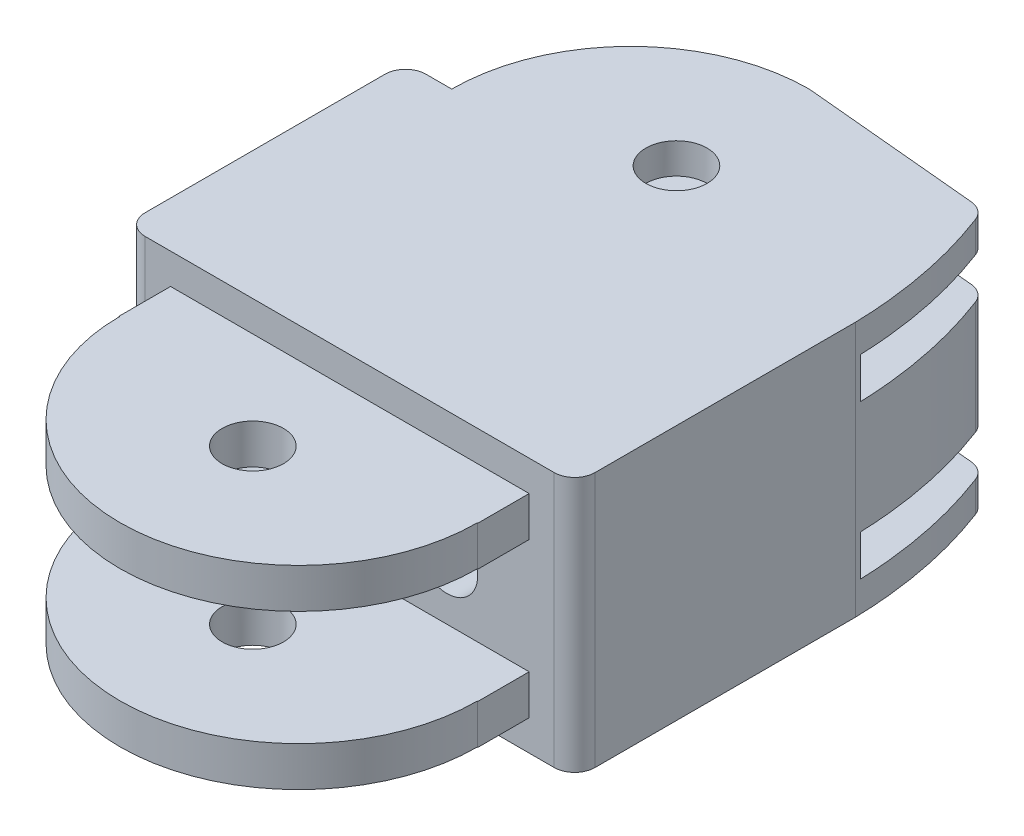
SolidWorks part; units mm, degrees
ref_plane "Front Plane" through (0, 0, 0) normal (0, 0, 1) x (1, 0, 0)
ref_plane "Top Plane" through (0, 0, 0) normal (0, 1, 0) x (1, 0, 0)
ref_plane "Right Plane" through (0, 0, 0) normal (1, 0, 0) x (0, 0, -1)
sketch "Sketch2" plane through (0, 0, 0) normal (0, 0, 1) x (1, 0, 0)
  line L0 (-24.2561, -24.0702) -> (-22.0061, -24.0702) construction
  line L1 (-24.2561, -17.8202) -> (-2.2017, -17.8202) construction
  line L2 (-24.2561, -17.8202) -> (-24.2561, -30.3202) construction
  line L3 (-24.2561, -30.3202) -> (-2.2017, -30.3202) construction
  line L4 (-2.2017, -17.8202) -> (-2.2017, -30.3202) construction
  line L5 (-2.2017, -24.0702) -> (-4.4517, -24.0702) construction
  line L6 (-22.0061, -24.0702) -> (-22.0061, -30.3202) construction
  line L7 (-4.4517, -24.0702) -> (-4.4517, -30.3202) construction
  line L8 (-24.2561, -17.8202) -> (-24.2561, -19.3148) construction
  line L9 (-24.2561, -19.3148) -> (-22.0061, -19.3148) construction
  line L10 (-2.2017, -17.8202) -> (-2.2017, -19.3148) construction
  line L11 (-2.2017, -19.3148) -> (-4.4517, -19.3148) construction
  line L12 (-2.2017, -30.3202) -> (-2.2017, -28.8202) construction
  line L13 (-2.2017, -28.8202) -> (-4.4517, -28.8202) construction
  line L14 (-24.2561, -30.3202) -> (-24.2561, -28.8202) construction
  line L15 (-24.2561, -28.8202) -> (-22.0061, -28.8202) construction
  line L17 (-22.0061, -28.8202) -> (-4.4517, -28.8202)
  line L18 (-22.0061, -28.8202) -> (-22.0061, -26.8702)
  line L19 (-22.0061, -26.8702) -> (-4.4517, -26.8702)
  line L20 (-4.4517, -28.8202) -> (-4.4517, -26.8702)
  line L21 (-22.0061, -28.8202) -> (-4.4517, -26.8702) construction
  line L22 (-22.0061, -26.8702) -> (-4.4517, -28.8202) construction
  line L23 (-22.0061, -19.3148) -> (-4.4517, -19.3148)
  line L24 (-22.0061, -19.3148) -> (-22.0061, -21.2648)
  line L25 (-22.0061, -21.2648) -> (-4.4517, -21.2648)
  line L26 (-4.4517, -19.3148) -> (-4.4517, -21.2648)
  line L27 (-22.0061, -19.3148) -> (-4.4517, -21.2648) construction
  line L28 (-22.0061, -21.2648) -> (-4.4517, -19.3148) construction
  point P19 (-13.2289, -27.8452)
  point P22 (-13.2289, -20.2898)
extrude "Boss-Extrude1" add sketch "Sketch2" along normal blind 8.75
sketch "Sketch3" plane through (0, -19.3148, 0) normal (0, 1, 0) x (1, 0, 0)
  line L0 (-4.4517, 0) -> (-22.0061, 0) construction
  line L1 (-4.4517, -8.75) -> (-22.0061, -8.75) construction
  arc A0 (-13.2289, -8.75) -> (-4.4789, 0) centre (-13.2289, 0) ccw
  arc A1 (-13.2289, -8.75) -> (-21.9789, 0) centre (-13.2289, 0) cw
  spline S0 degree 2 poles (-22.0061, -8.75) (-13.2289, -12.4735) (-4.4517, -8.75) knots 0 0 0 1 1 1
  spline S1 degree 2 poles (-21.9789, 0) (-25.927, -4.2429) (-22.0061, -8.75) knots 0 0 0 1 1 1
  spline S2 degree 2 poles (-4.4789, 0) (1.1383, -4.1517) (-4.4517, -8.75) knots 0 0 0 1 1 1
extrude "Cut-Extrude1" cut sketch "Sketch3" against normal through all contours S0 S2 A0 A1 S1
sketch "Sketch4" plane through (0, 0, 0) normal (0, 0, -1) x (-1, 0, 0)
  line L0 (22.0061, -19.3148) -> (24.2561, -19.3148) construction
  line L1 (22.0061, -19.3148) -> (4.4789, -19.3148) construction
  line L2 (22.0061, -19.3148) -> (22.0061, -28.8202) construction
  line L3 (22.0061, -28.8202) -> (4.4789, -28.8202) construction
  line L4 (4.4789, -19.3148) -> (4.4789, -28.8202) construction
  line L5 (22.0061, -19.3148) -> (4.4789, -28.8202) construction
  line L6 (22.0061, -28.8202) -> (4.4789, -19.3148) construction
  line L7 (24.2561, -19.3148) -> (24.2561, -17.8148) construction
  line L8 (4.4789, -28.8202) -> (2.2289, -28.8202) construction
  line L9 (2.2289, -28.8202) -> (2.2289, -30.3202) construction
  line L11 (24.2561, -17.8148) -> (2.2289, -17.8148)
  line L12 (24.2561, -17.8148) -> (24.2561, -30.3202)
  line L13 (24.2561, -30.3202) -> (2.2289, -30.3202)
  line L14 (2.2289, -17.8148) -> (2.2289, -30.3202)
  line L15 (24.2561, -17.8148) -> (2.2289, -30.3202) construction
  line L16 (24.2561, -30.3202) -> (2.2289, -17.8148) construction
  point P4 (13.2425, -24.0675)
  point P14 (13.2425, -24.0675)
extrude "Boss-Extrude2" add sketch "Sketch4" along normal blind 25 contours L12 L13 L14 L11
sketch "Sketch5" plane through (0, -19.3148, 0) normal (0, 1, 0) x (1, 0, 0)
  line L0 (-13.2289, -8.75) -> (-13.2289, -2.25) construction
  arc A0 (-21.9789, 0) -> (-4.4789, 0) centre (-13.2289, 0) ccw construction
  circle A1 centre (-13.2289, -2.25) radius 1.5
extrude "Cut-Extrude2" cut sketch "Sketch5" against normal blind 12 contours A1
sketch "Sketch6" plane through (0, 0, 0) normal (0, 0, 1) x (1, 0, 0)
  line L0 (-24.2561, -30.3202) -> (-2.2289, -30.3202)
  line L1 (-2.2289, -30.3202) -> (-2.2289, -17.8148)
  line L2 (-2.2289, -17.8148) -> (-24.2561, -17.8148)
  line L3 (-24.2561, -17.8148) -> (-24.2561, -30.3202)
  line L4 (-22.0061, -28.8202) -> (-4.4517, -28.8202)
  line L5 (-4.4517, -28.8202) -> (-4.4517, -26.8702)
  line L6 (-4.4517, -28.8202) -> (-4.4517, -26.8702) construction
  line L7 (-4.4517, -26.8702) -> (-22.0061, -26.8702)
  line L8 (-22.0061, -28.8202) -> (-22.0061, -26.8702)
  line L9 (-22.0061, -21.2648) -> (-22.0061, -19.3148)
  line L10 (-22.0061, -19.3148) -> (-4.4517, -19.3148)
  line L11 (-4.4517, -19.3148) -> (-4.4517, -21.2648)
  line L12 (-4.4517, -21.2648) -> (-22.0061, -21.2648)
extrude "Cut-Extrude3" cut sketch "Sketch6" against normal blind 2.5
sketch "Sketch7" plane through (0, -17.8148, 0) normal (0, 1, 0) x (1, 0, 0)
  line L0 (-2.2289, 25) -> (-2.2289, 2.5) construction
  line L1 (-24.2561, 25) -> (-2.2289, 25) construction
  line L3 (-21.9925, 16.25) -> (-24.2561, 16.25)
  line L7 (-13.2425, 25) -> (-3.8818, 24.1286)
  circle A0 centre (-13.2425, 18.5) radius 1.5
  arc A1 (-13.2425, 25) -> (-21.9925, 16.25) centre (-13.2425, 16.25) ccw
  spline S0 degree 3 poles (-24.2561, 16.25) (-34.3688, 22.1782) (-14.7123, 52.0329) (16.6293, 22.4638) (-2.2289, 16.25) knots 0 0 0 0 0.431251 1 1 1 1
  spline S1 degree 2 poles (-3.8818, 24.1286) (-2.3288, 20.3726) (-2.2289, 16.25) knots 0 0 0 1 1 1
extrude "Cut-Extrude4" cut sketch "Sketch7" against normal blind 13
sketch "Sketch8" plane through (0, 0, -2.5) normal (0, 0, 1) x (1, 0, 0)
  line L0 (-24.2561, -24.0675) -> (-18.0111, -24.0675) construction
  line L1 (-24.2561, -17.8148) -> (-24.2561, -30.3202) construction
  line L2 (-2.2289, -24.0675) -> (-8.474, -24.0675) construction
  line L3 (-2.2289, -30.3202) -> (-2.2289, -17.8148) construction
  line L4 (-4.4517, -21.2648) -> (-4.4517, -24.0675) construction
  line L5 (-4.4517, -24.0675) -> (-8.474, -24.0675) construction
  circle A0 centre (-18.0111, -24.0675) radius 1.5
  circle A1 centre (-8.474, -24.0675) radius 1.5
extrude "Cut-Extrude5" cut sketch "Sketch8" against normal blind 28
fillet "Fillet3" radius 1 4 edges at (-24.2561, -24.0675, -2.5) (-24.2561, -24.0675, -16.25) (-2.2289, -24.0675, -2.5) (-3.8818, -24.0675, -24.1286)
ref_plane "Plane4" through (0, 0, -32.5) normal (0, 0, 1) x (1, 0, 0)
sketch "Sketch9" plane through (0, 0, -32.5) normal (0, 0, 1) x (1, 0, 0)
  line L0 (-24.2561, -17.8148) -> (-24.2561, -19.3148) construction
  line L1 (-24.2561, -17.8148) -> (-2.2289, -17.8148) construction
  line L2 (-24.2561, -17.8148) -> (-24.2561, -30.3202) construction
  line L3 (-24.2561, -30.3202) -> (-2.2289, -30.3202) construction
  line L4 (-2.2289, -17.8148) -> (-2.2289, -30.3202) construction
  line L5 (-24.2561, -17.8148) -> (-2.2289, -30.3202) construction
  line L6 (-24.2561, -30.3202) -> (-2.2289, -17.8148) construction
  line L7 (-24.2561, -30.3202) -> (-24.2561, -28.8361) construction
  line L8 (-24.2561, -19.3148) -> (-2.2289, -19.3148)
  line L9 (-24.2561, -19.3148) -> (-24.2561, -21.3148)
  line L10 (-24.2561, -21.3148) -> (-2.2289, -21.3148)
  line L11 (-2.2289, -19.3148) -> (-2.2289, -21.3148)
  line L12 (-24.2561, -19.3148) -> (-2.2289, -21.3148) construction
  line L13 (-24.2561, -21.3148) -> (-2.2289, -19.3148) construction
  line L15 (-24.2561, -28.8361) -> (-2.2289, -28.8361)
  line L16 (-24.2561, -28.8361) -> (-24.2561, -26.8361)
  line L17 (-24.2561, -26.8361) -> (-2.2289, -26.8361)
  line L18 (-2.2289, -28.8361) -> (-2.2289, -26.8361)
  line L19 (-24.2561, -28.8361) -> (-2.2289, -26.8361) construction
  line L20 (-24.2561, -26.8361) -> (-2.2289, -28.8361) construction
  point P4 (-13.2425, -24.0675)
  point P8 (-13.2425, -20.3148)
  point P13 (-13.2425, -27.8361)
extrude "Cut-Extrude6" cut sketch "Sketch9" along normal blind 16
